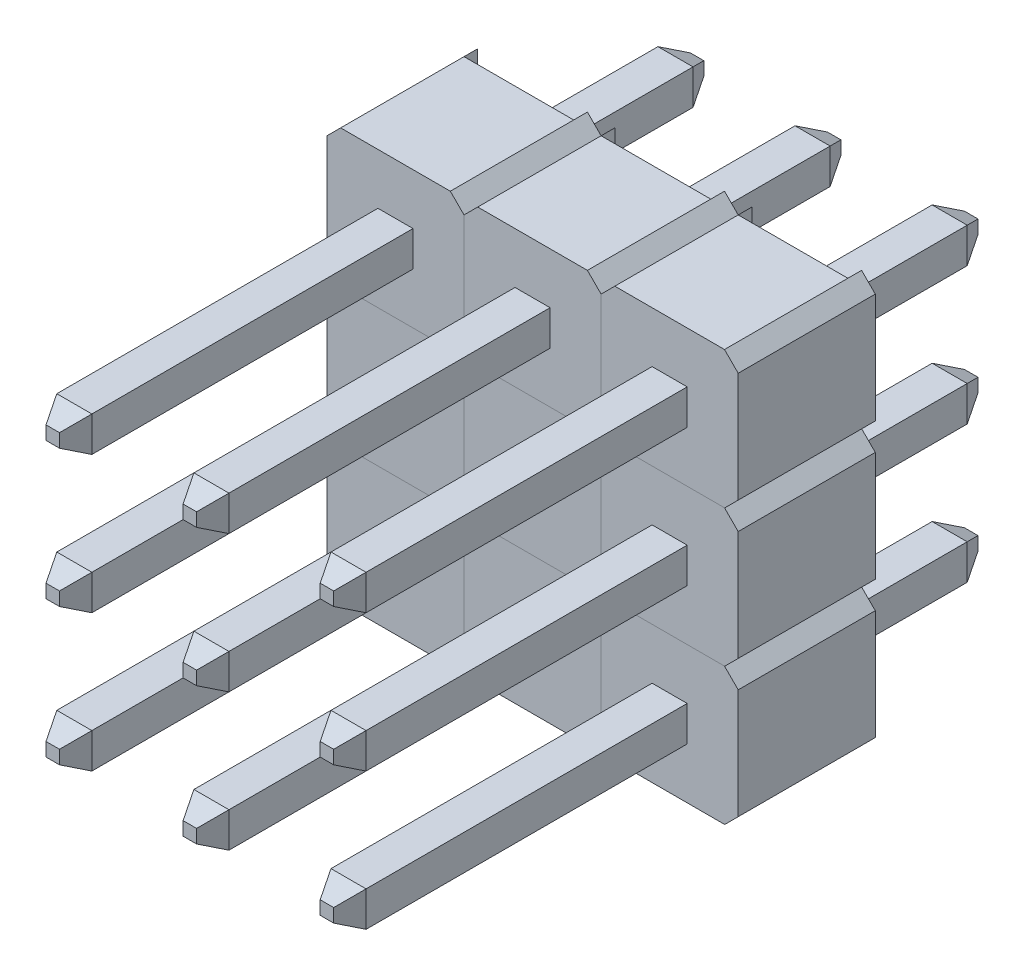
SolidWorks part; units mm, degrees
other "Markup1"
sketch "Sketch9" plane through (-1.27, 3.81, 8.89) normal (-0.6109, 0.2412, 0.7541) x (-0.1554, -0.9705, 0.1846)
ref_plane "Front Plane" through (0, 0, 0) normal (0, 0, 1) x (1, 0, 0)
ref_plane "Top Plane" through (0, 0, 0) normal (0, 1, 0) x (1, 0, 0)
ref_plane "Right Plane" through (0, 0, 0) normal (1, 0, 0) x (0, 0, -1)
ref_plane "Plane1" through (0, 0, 2.54) normal (0, 0, 1) x (1, 0, 0)
sketch "Sketch1" plane through (0, 0, 2.54) normal (0, 0, 1) x (1, 0, 0)
  line L0 (1.27, -1.016) -> (1.27, 3.556)
  line L1 (1.27, 3.556) -> (1.016, 3.81)
  line L2 (1.016, 3.81) -> (-1.016, 3.81)
  line L3 (-1.016, 3.81) -> (-1.27, 3.556)
  line L4 (-1.27, 3.556) -> (-1.27, -1.016)
  line L5 (-1.27, -1.016) -> (-1.016, -1.27)
  line L6 (-1.016, -1.27) -> (1.016, -1.27)
  line L7 (1.016, -1.27) -> (1.27, -1.016)
extrude "Boss-Extrude1" add sketch "Sketch1" against normal blind 2.286
sketch "Sketch2" plane through (0, 0, 0.254) normal (0, 0, -1) x (-1, 0, 0)
  line L0 (1.016, -1.27) -> (1.016, 3.81)
  line L1 (1.016, 3.81) -> (1.27, 3.556)
  line L2 (1.27, 3.556) -> (1.27, -1.016)
  line L3 (1.27, -1.016) -> (1.016, -1.27)
extrude "Boss-Extrude2" add sketch "Sketch2" along normal blind 0.254
sketch "Sketch3" plane through (0, 0, 0.254) normal (0, 0, -1) x (-1, 0, 0)
  line L0 (-1.27, -1.016) -> (-1.27, 3.556)
  line L1 (-1.27, 3.556) -> (-1.016, 3.81)
  line L2 (-1.016, 3.81) -> (-1.016, -1.27)
  line L3 (-1.016, -1.27) -> (-1.27, -1.016)
extrude "Boss-Extrude3" add sketch "Sketch3" along normal blind 0.254
sketch "Sketch4" plane through (0, 0, 0.254) normal (0, 0, -1) x (-1, 0, 0)
  line L0 (0.325, 0.325) -> (0.325, -0.325)
  line L1 (0.325, -0.325) -> (-0.325, -0.325)
  line L2 (-0.325, -0.325) -> (-0.325, 0.325)
  line L3 (-0.325, 0.325) -> (0.325, 0.325)
extrude "Boss-Extrude4" add sketch "Sketch4" along normal blind 3.302
sketch "Sketch5" plane through (0, 0, 2.54) normal (0, 0, 1) x (1, 0, 0)
  line L0 (0.325, 0.325) -> (0.325, -0.325)
  line L1 (0.325, -0.325) -> (-0.325, -0.325)
  line L2 (-0.325, -0.325) -> (-0.325, 0.325)
  line L3 (-0.325, 0.325) -> (0.325, 0.325)
extrude "Boss-Extrude5" add sketch "Sketch5" along normal blind 6.35
sketch "Sketch6" plane through (0, 0, 0.254) normal (0, 0, -1) x (-1, 0, 0)
  line L0 (-0.325, 2.215) -> (-0.325, 2.865)
  line L1 (-0.325, 2.865) -> (0.325, 2.865)
  line L2 (0.325, 2.865) -> (0.325, 2.215)
  line L3 (0.325, 2.215) -> (-0.325, 2.215)
extrude "Boss-Extrude6" add sketch "Sketch6" along normal blind 3.302
sketch "Sketch7" plane through (0, 0, 2.54) normal (0, 0, 1) x (1, 0, 0)
  line L0 (-0.325, 2.865) -> (0.325, 2.865)
  line L1 (0.325, 2.865) -> (0.325, 2.215)
  line L2 (0.325, 2.215) -> (-0.325, 2.215)
  line L3 (-0.325, 2.215) -> (-0.325, 2.865)
extrude "Boss-Extrude7" add sketch "Sketch7" along normal blind 6.35
chamfer "Chamfer1" distance 0.2 angle 63.435 16 edges at (0.325, 2.54, 8.89) (0, 2.865, 8.89) (-0.325, 2.54, 8.89) (0, 2.215, 8.89) (0, 2.865, -3.048) (0.325, 2.54, -3.048) (-0.325, 2.54, -3.048) (0, 2.215, -3.048) (0, -0.325, 8.89) (0.325, 0, 8.89) (-0.325, 0, 8.89) (0, 0.325, 8.89) (0, -0.325, -3.048) (-0.325, 0, -3.048) (0, 0.325, -3.048) (0.325, 0, -3.048)
ref_plane "Plane2" through (0, 1.27, 0) normal (0, 1, 0) x (1, 0, 0)
sketch "Sketch8" plane through (0, 1.27, 0) normal (0, 1, 0) x (1, 0, 0)
  line L1 (-1.712, 3.9545) -> (1.9605, 3.9545)
  line L2 (-1.712, 3.9545) -> (-1.712, -9.6585)
  line L3 (-1.712, -9.6585) -> (1.9605, -9.6585)
  line L4 (1.9605, 3.9545) -> (1.9605, -9.6585)
extrude "Cut-Extrude1" cut sketch "Sketch8" against normal blind 10
chamfer "Chamfer2" distance 0.25 angle 45 2 edges at (1.27, 1.27, 1.27) (-1.27, 1.27, 1.27)
pattern_linear "LPattern1" count 3 spacing 2.54 along (-1, 0, 0) of bodies 110
pattern_linear "LPattern2" count 3 spacing 2.54 along (0, -1, 0) of bodies 112 111 110
